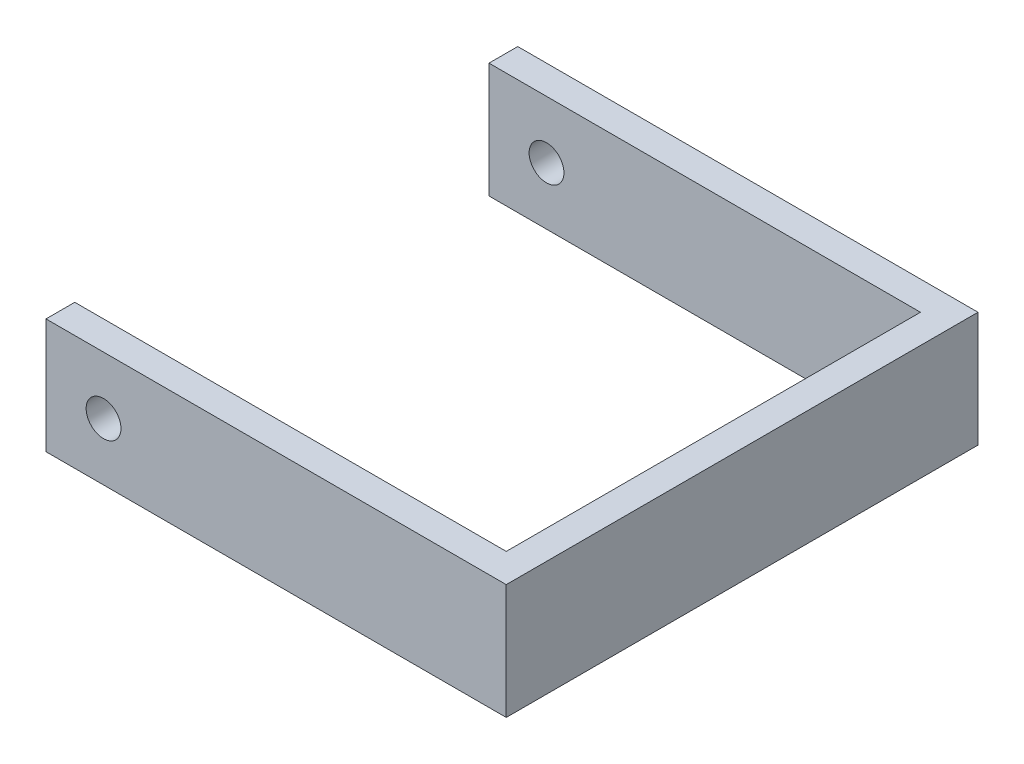
SolidWorks part; units mm, degrees
ref_plane "Front Plane" through (0, 0, 0) normal (0, 0, 1) x (1, 0, 0)
ref_plane "Top Plane" through (0, 0, 0) normal (0, 1, 0) x (1, 0, 0)
ref_plane "Right Plane" through (0, 0, 0) normal (1, 0, 0) x (0, 0, -1)
sketch "Sketch2" plane through (0, 0, 0) normal (0, 1, 0) x (1, 0, 0)
  line L0 (-53, 41) -> (27, 41)
  line L1 (27, 41) -> (27, -41)
  line L2 (27, -41) -> (-53, -41)
  line L3 (-53, -41) -> (-53, -36)
  line L4 (-53, -36) -> (22, -36)
  line L5 (22, -36) -> (22, 36)
  line L6 (22, 36) -> (-53, 36)
  line L7 (-53, 36) -> (-53, 41)
  dimension "D1" = 82
  dimension "D2" = 5
  dimension "D3" = 5
  dimension "D4" = 5
  dimension "D5" = 80
  dimension "D6" = 80
  dimension "D7" = 41
  dimension "D8" = 22
extrude "Boss-Extrude1" add sketch "Sketch2" along normal blind 20
sketch "Sketch3" plane through (0, 0, 41) normal (0, 0, 1) x (1, 0, 0)
  line L0 (-53, 20) -> (-53, 0) construction
  line L1 (-53, 20) -> (27, 20) construction
  circle A0 centre (-43, 10) radius 3.025
  dimension "D1" = 6.05
  dimension "D2" = 10
  dimension "D3" = 10
extrude "Cut-Extrude1" cut sketch "Sketch3" against normal up to surface (77 mm away)
mirror "Mirror1" about plane through (0, 0, 0) normal (0, 0, 1) of "Cut-Extrude1"
